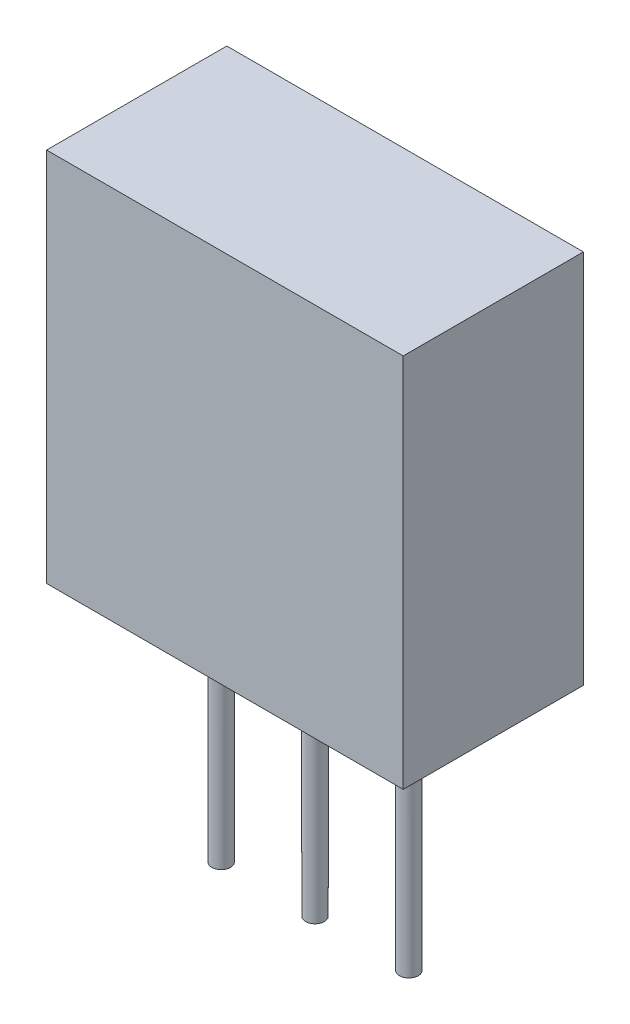
SolidWorks part; units mm, degrees
ref_plane "Front Plane" through (0, 0, 0) normal (0, 0, 1) x (1, 0, 0)
ref_plane "Top Plane" through (0, 0, 0) normal (0, 1, 0) x (1, 0, 0)
ref_plane "Right Plane" through (0, 0, 0) normal (1, 0, 0) x (0, 0, -1)
sketch "Sketch1" plane through (0, 0, 0) normal (0, 0, 1) x (1, 0, 0)
  line L1 (0, 0) -> (9.5, 0)
  line L2 (0, 0) -> (0, 10)
  line L3 (0, 10) -> (9.5, 10)
  line L4 (9.5, 0) -> (9.5, 10)
  dimension "D1" = 9.5
  dimension "D2" = 10
extrude "Boss-Extrude1" add sketch "Sketch1" along normal blind 4.8
sketch "Sketch2" plane through (0, 0, 0) normal (0, -1, 0) x (-1, 0, 0)
  line L0 (0, -2.4) -> (-9.5, -2.4) construction
  line L1 (0, -4.8) -> (0, 0) construction
  line L2 (-9.5, -4.8) -> (-9.5, 0) construction
  circle A0 centre (-4.75, -2.4) radius 0.25
  circle A1 centre (-2.25, -2.4) radius 0.25
  circle A2 centre (-7.25, -2.4) radius 0.25
  point P10 (-2.3662, -2.4)
  point P13 (-7.0107, -2.4)
  point P14 (0, 0)
  point P15 (0, 0)
  point P16 (0, 0)
  point P17 (0, 0)
  point P18 (0, 0)
  point P19 (0, 0)
  point P20 (0, 0)
  dimension "D1" = 0.5
  dimension "D2" = 2.5
  dimension "D3" = 2.5
extrude "Boss-Extrude2" add sketch "Sketch2" along normal blind 6.5
